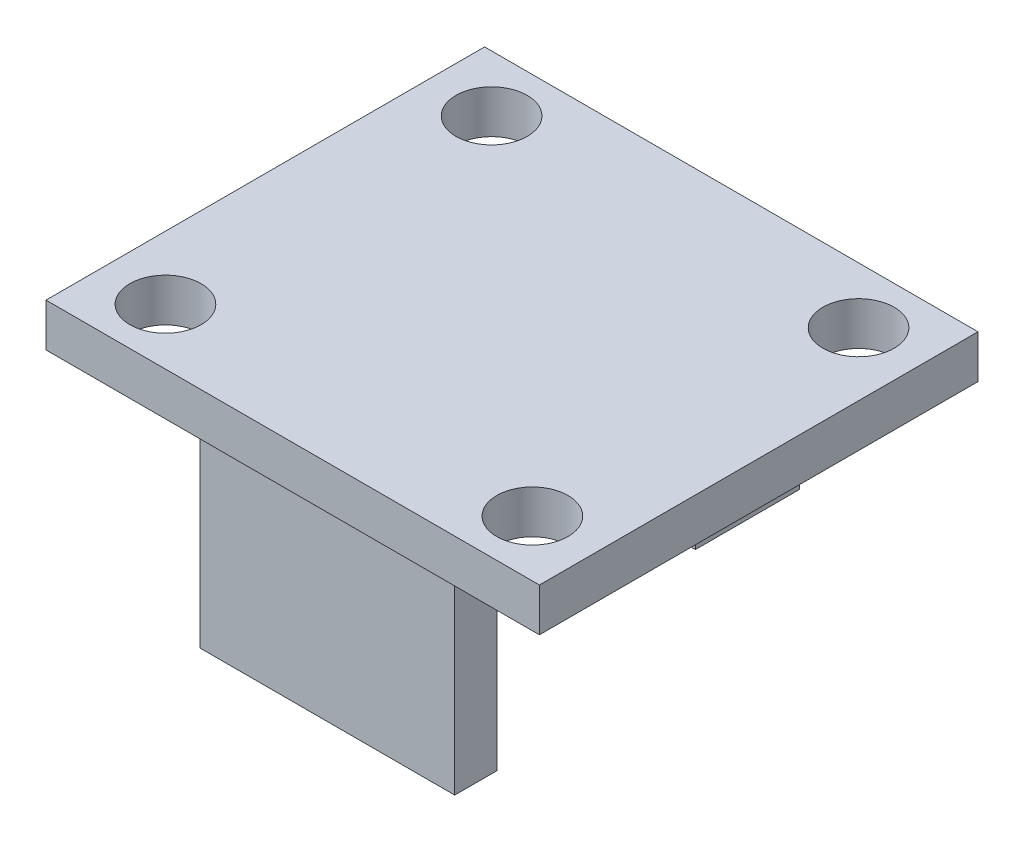
SolidWorks part; units mm, degrees
ref_plane "Front Plane" through (0, 0, 0) normal (0, 0, 1) x (1, 0, 0)
ref_plane "Top Plane" through (0, 0, 0) normal (0, 1, 0) x (1, 0, 0)
ref_plane "Right Plane" through (0, 0, 0) normal (1, 0, 0) x (0, 0, -1)
sketch "Sketch1" plane through (0, 0, 0) normal (0, 1, 0) x (1, 0, 0)
  line L1 (11.43, -10.16) -> (-11.43, -10.16)
  line L2 (11.43, -10.16) -> (11.43, 10.16)
  line L3 (11.43, 10.16) -> (-11.43, 10.16)
  line L4 (-11.43, -10.16) -> (-11.43, 10.16)
  line L5 (11.43, -10.16) -> (-11.43, 10.16) construction
  line L6 (11.43, 10.16) -> (-11.43, -10.16) construction
  line L7 (8.5, -7.5556) -> (-8.5, -7.5556) construction
  line L8 (8.5, -7.5556) -> (8.5, 7.5556) construction
  line L9 (8.5, 7.5556) -> (-8.5, 7.5556) construction
  line L10 (-8.5, -7.5556) -> (-8.5, 7.5556) construction
  line L11 (8.5, -7.5556) -> (-8.5, 7.5556) construction
  line L12 (8.5, 7.5556) -> (-8.5, -7.5556) construction
  circle A0 centre (-8.5, 7.5556) radius 1.65
  circle A1 centre (8.5, 7.5556) radius 1.65
  circle A2 centre (-8.5, -7.5556) radius 1.65
  circle A3 centre (8.5, -7.5556) radius 1.65
  point P0 (0, 0)
  point P6 (0, 0)
  dimension "D3" = 3.3
  dimension "D1" = 22.86
  dimension "D2" = 20.32
  dimension "D4" = 17
extrude "Boss-Extrude1" add sketch "Sketch1" along normal blind 2
sketch "Sketch2" plane through (0, 0, 0) normal (0, -1, 0) x (1, 0, 0)
  line L1 (-5.8981, 6.5863) -> (5.8981, 6.5863)
  line L2 (-5.8981, 6.5863) -> (-5.8981, 8.5523)
  line L3 (-5.8981, 8.5523) -> (5.8981, 8.5523)
  line L4 (5.8981, 6.5863) -> (5.8981, 8.5523)
  line L5 (-5.8981, 6.5863) -> (5.8981, 8.5523) construction
  line L6 (-5.8981, 8.5523) -> (5.8981, 6.5863) construction
  point P0 (0, 7.5693)
extrude "Boss-Extrude2" add sketch "Sketch2" along normal blind 10
sketch "Sketch3" plane through (0, 0, 0) normal (0, -1, 0) x (1, 0, 0)
  line L1 (-3.6231, -9.7038) -> (3.6231, -9.7038)
  line L2 (-3.6231, -9.7038) -> (-3.6231, -4.873)
  line L3 (-3.6231, -4.873) -> (3.6231, -4.873)
  line L4 (3.6231, -9.7038) -> (3.6231, -4.873)
  line L5 (-3.6231, -9.7038) -> (3.6231, -4.873) construction
  line L6 (-3.6231, -4.873) -> (3.6231, -9.7038) construction
  point P0 (0, -7.2884)
extrude "Boss-Extrude3" add sketch "Sketch3" along normal blind 8
